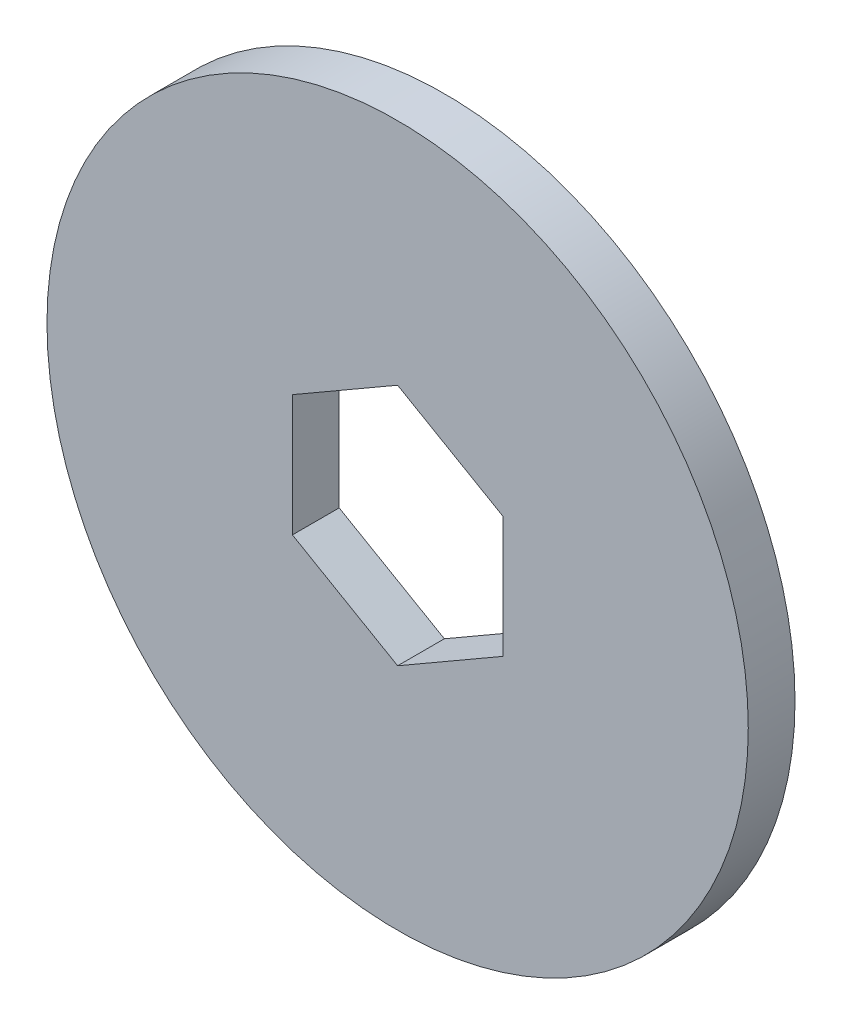
SolidWorks part; units mm, degrees
ref_plane "Front Plane" through (0, 0, 0) normal (0, 0, 1) x (1, 0, 0)
ref_plane "Top Plane" through (0, 0, 0) normal (0, 1, 0) x (1, 0, 0)
ref_plane "Right Plane" through (0, 0, 0) normal (1, 0, 0) x (0, 0, -1)
sketch "Model" plane through (0, 0, 0) normal (0, 0, 1) x (1, 0, 0)
  line L0 (628.8, -184.2058) -> (628.8, -199.7942)
  line L1 (628.8, -199.7942) -> (642.3, -207.5885)
  line L2 (642.3, -207.5885) -> (655.8, -199.7942)
  line L3 (655.8, -199.7942) -> (655.8, -184.2058)
  line L4 (655.8, -184.2058) -> (642.3, -176.4115)
  line L5 (642.3, -176.4115) -> (628.8, -184.2058)
  circle A0 centre (642.3, -192) radius 25
extrude "Boss-Extrude1" add sketch "Model" along normal blind 6
sketch "Sketch2" plane through (0, 0, 6) normal (0, 0, 1) x (1, 0, 0)
  circle A0 centre (642.3, -192) radius 25
  circle A1 centre (642.3, -192) radius 45
  circle M2 centre (642.3, -192) radius 25
extrude "Boss-Extrude2" add sketch "Sketch2" against normal blind 6 contours A1 M2
